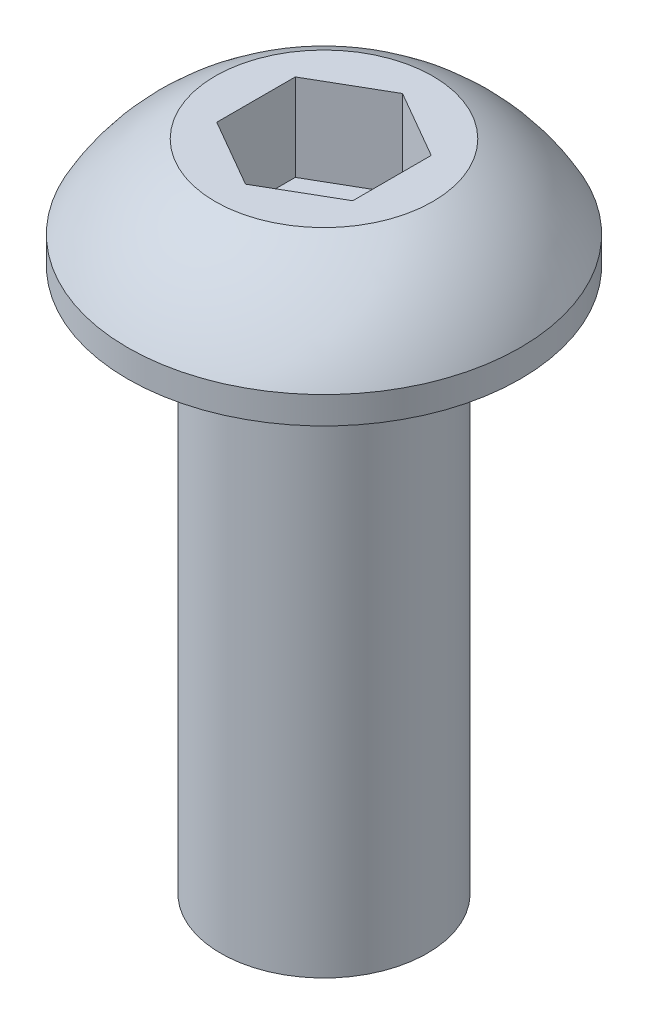
SolidWorks part; units mm, degrees
material "Alloy Steel"
ref_plane "Front Plane" through (0, 0, 0) normal (0, 0, 1) x (1, 0, 0)
ref_plane "Top Plane" through (0, 0, 0) normal (0, 1, 0) x (1, 0, 0)
ref_plane "Right Plane" through (0, 0, 0) normal (1, 0, 0) x (0, 0, -1)
sketch "Sketch1" plane through (0, 0, 0) normal (0, 0, 1) x (1, 0, 0)
  line L0 (4.5847, 0) -> (4.5847, 0.635)
  line L1 (4.5847, 0) -> (0, 0)
  line L2 (0, 0) -> (0, 2.5654)
  line L3 (0, 2.5654) -> (2.54, 2.5654)
  arc A0 (2.54, 2.5654) -> (4.5847, 0.635) centre (0.5758, -1.5632) cw
  dimension "D4" = 4.572
  dimension "D1" = 4.5847
  dimension "D2" = 2.5654
  dimension "D3" = 0.635
  dimension "D5" = 2.54
revolve "Revolve1" add sketch "Sketch1" angle 360 about L2
sketch "Sketch2" plane through (0, 2.5654, 0) normal (0, 1, 0) x (-1, 0, 0)
  line L1 (0, 1.8331) -> (-1.5875, 0.9165)
  line L2 (-1.5875, 0.9165) -> (-1.5875, -0.9165)
  line L3 (-1.5875, -0.9165) -> (0, -1.8331)
  line L4 (0, -1.8331) -> (1.5875, -0.9165)
  line L5 (1.5875, -0.9165) -> (1.5875, 0.9165)
  line L6 (1.5875, 0.9165) -> (0, 1.8331)
  circle A0 centre (0, 0) radius 1.5875 construction
  dimension "D1" = 3.175
extrude "Cut-Extrude1" cut sketch "Sketch2" against normal blind 2.032
sketch "Sketch3" plane through (0, 0, 0) normal (0, -1, 0) x (1, 0, 0)
  circle A0 centre (0, 0) radius 2.413
  dimension "D1" = 4.826
extrude "Extrude1" add sketch "Sketch3" along normal blind 12.7
